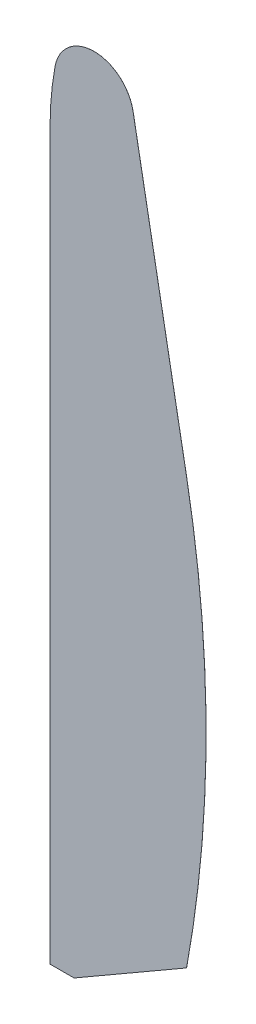
SolidWorks part; units mm, degrees
ref_plane "Front Plane" through (0, 0, 0) normal (1, 0, 0) x (0, 1, 0)
ref_plane "Top Plane" through (0, 0, 0) normal (0, 0, 1) x (0, 1, 0)
ref_plane "Right Plane" through (0, 0, 0) normal (0, 1, 0) x (-1, 0, 0)
sketch "Sketch1" plane through (0, 0, 0) normal (0, 0, 1) x (0, 1, 0)
  line L0 (0, 0) -> (0, 50000) construction
  line L1 (0, 0) -> (50000, 0) construction
  line L2 (143.5634, 601.065) -> (1381.2364, 932.6984) construction
  line L3 (0, 0) -> (151.125, 0)
  line L4 (0, 0) -> (0, -5)
  line L5 (0, -5) -> (13.5316, -28.4375)
  line L6 (162.5, -17.2924) -> (102.1982, -28.4375)
  line L7 (0, 0) -> (57.8649, -32.5)
  line L8 (0, 0) -> (162.5, -17.2924)
  arc A0 (151.125, 0) -> (162.5, -1.0424) centre (151.125, -62.5878) cw
  arc A1 (162.5, -1.0424) -> (162.5, -17.2924) centre (160.9983, -9.1674) cw
  arc A2 (13.5316, -28.4375) -> (102.1982, -28.4375) centre (57.8649, 211.4316) ccw
  dimension "D1" = 5
  dimension "D2" = 28.4375
  dimension "D3" = 151.125
  dimension "Span" = 162.5
  dimension "Chord" = 32.5
  dimension "D4" = 30
  dimension "D5" = 16.25
extrude "Boss-Extrude1" add sketch "Sketch1" along normal blind 0.01 contours L6 A2 L5 L4 L3 A0 A1
equation "\"D3@Sketch1\"=\"Span@Sketch1\"*0.93"
equation "\"D2@Sketch1\"=\"Chord@Sketch1\"*0.875"
equation "\"Chord@Sketch1\"=\"Span@Sketch1\"/5"
equation "\"D5@Sketch1\"=\"Chord@Sketch1\"/2"
